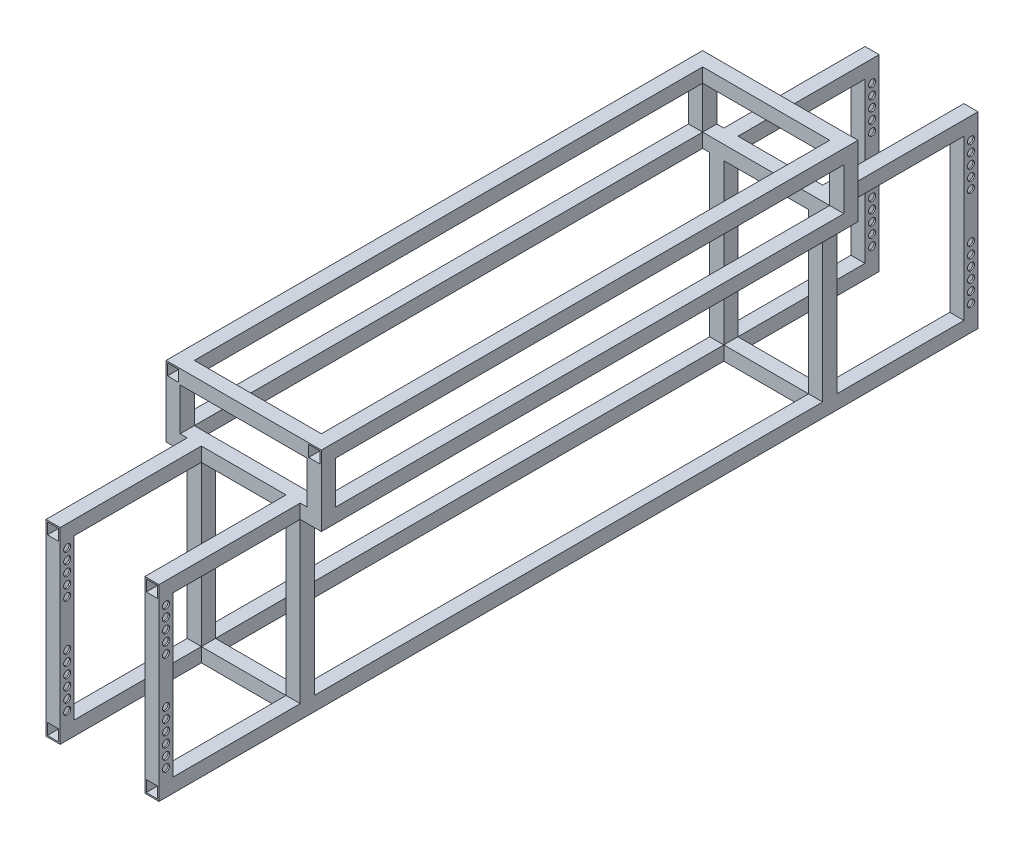
SolidWorks part; units mm, degrees
ref_plane "Płaszczyzna przednia" through (0, 0, 0) normal (0, 0, 1) x (1, 0, 0)
ref_plane "Płaszczyzna górna" through (0, 0, 0) normal (0, 1, 0) x (1, 0, 0)
ref_plane "Płaszczyzna prawa" through (0, 0, 0) normal (1, 0, 0) x (0, 0, -1)
sketch "Szkic1" plane through (0, 0, 0) normal (0, 0, 1) x (1, 0, 0)
  line L0 (-8, 8) -> (8, 8)
  line L1 (-10, -10) -> (10, -10)
  line L2 (-10, -10) -> (-10, 10)
  line L3 (-10, 10) -> (10, 10)
  line L4 (10, -10) -> (10, 10)
  line L5 (-10, -10) -> (10, 10) construction
  line L6 (-10, 10) -> (10, -10) construction
  line L7 (8, -8) -> (8, 8)
  line L8 (-8, -8) -> (8, -8)
  line L9 (-8, -8) -> (-8, 8)
  point P0 (0, 0)
  dimension "D1" = 20
  dimension "D2" = 20
  dimension "D3" = 2
extrude "Dodanie-wyciągnięcie1" add sketch "Szkic1" along normal blind 760
sketch "Szkic2" plane through (10, 0, 0) normal (1, 0, 0) x (0, 0, -1)
  line L0 (-760, -10) -> (0, -10) construction
  line L1 (-760, 10) -> (-740, 10)
  line L2 (-760, 10) -> (-760, -10)
  line L3 (-760, -10) -> (-740, -10)
  line L4 (-740, 10) -> (-740, -10)
  line L5 (-758, 8) -> (-742, 8)
  line L6 (-742, 8) -> (-742, -8)
  line L7 (-758, -8) -> (-742, -8)
  line L8 (-758, 8) -> (-758, -8)
  dimension "D1" = 20
  dimension "D2" = 2
extrude "Dodanie-wyciągnięcie2" add sketch "Szkic2" along normal blind 180
sketch "Szkic3" plane through (10, 0, 0) normal (1, 0, 0) x (0, 0, -1)
  line L0 (-740, -10) -> (0, -10) construction
  line L1 (0, 10) -> (-20, 10)
  line L2 (0, 10) -> (0, -10)
  line L3 (0, -10) -> (-20, -10)
  line L4 (-20, 10) -> (-20, -10)
  line L5 (-2, 8) -> (-18, 8)
  line L6 (-18, 8) -> (-18, -8)
  line L7 (-2, -8) -> (-18, -8)
  line L8 (-2, 8) -> (-2, -8)
  dimension "D1" = 20
  dimension "D2" = 2
extrude "Dodanie-wyciągnięcie3" add sketch "Szkic3" along normal blind 180
sketch "Szkic4" plane through (0, 0, 760) normal (0, 0, 1) x (1, 0, 0)
  line L0 (192, 8) -> (208, 8)
  line L1 (190, 10) -> (210, 10)
  line L2 (190, 10) -> (190, -10)
  line L3 (190, -10) -> (210, -10)
  line L4 (210, 10) -> (210, -10)
  line L5 (208, 8) -> (208, -8)
  line L6 (192, -8) -> (208, -8)
  line L7 (192, 8) -> (192, -8)
  dimension "D1" = 20
  dimension "D2" = 20
  dimension "D3" = 2
extrude "Dodanie-wyciągnięcie4" add sketch "Szkic4" against normal blind 760
sketch "Szkic5" plane through (0, -10, 0) normal (0, -1, 0) x (1, 0, 0)
  line L0 (-8, 758) -> (8, 758)
  line L1 (-10, 760) -> (10, 760)
  line L2 (-10, 760) -> (-10, 740)
  line L3 (-10, 740) -> (10, 740)
  line L4 (10, 760) -> (10, 740)
  line L5 (210, 760) -> (190, 760)
  line L6 (210, 760) -> (210, 740)
  line L7 (210, 740) -> (190, 740)
  line L8 (190, 760) -> (190, 740)
  line L9 (-10, 0) -> (10, 0)
  line L10 (-10, 0) -> (-10, 20)
  line L11 (-10, 20) -> (10, 20)
  line L12 (10, 0) -> (10, 20)
  line L13 (210, 0) -> (190, 0)
  line L14 (210, 0) -> (210, 20)
  line L15 (210, 20) -> (190, 20)
  line L16 (190, 0) -> (190, 20)
  line L17 (8, 758) -> (8, 742)
  line L18 (-8, 742) -> (8, 742)
  line L19 (-8, 758) -> (-8, 742)
  line L20 (208, 758) -> (192, 758)
  line L21 (192, 758) -> (192, 742)
  line L22 (208, 742) -> (192, 742)
  line L23 (208, 758) -> (208, 742)
  line L24 (208, 18) -> (192, 18)
  line L25 (192, 2) -> (192, 18)
  line L26 (208, 2) -> (192, 2)
  line L27 (208, 2) -> (208, 18)
  line L28 (-8, 18) -> (8, 18)
  line L29 (8, 2) -> (8, 18)
  line L30 (-8, 2) -> (8, 2)
  line L31 (-8, 2) -> (-8, 18)
  dimension "D1" = 2
extrude "Dodanie-wyciągnięcie5" add sketch "Szkic5" along normal blind 80
sketch "Szkic6" plane through (0, 0, 20) normal (0, 0, 1) x (1, 0, 0)
  line L0 (210, -90) -> (210, 10) construction
  line L1 (210, -90) -> (190, -90)
  line L2 (210, -90) -> (210, -70)
  line L3 (210, -70) -> (190, -70)
  line L4 (190, -90) -> (190, -70)
  line L5 (190, -90) -> (190, -10) construction
  line L6 (-10, 10) -> (-10, -90) construction
  line L7 (-10, -90) -> (10, -90)
  line L8 (-10, -90) -> (-10, -70)
  line L9 (-10, -70) -> (10, -70)
  line L10 (10, -90) -> (10, -70)
  line L11 (10, -90) -> (10, -10) construction
  line L12 (10, -10) -> (190, -10) construction
  line L13 (208, -72) -> (192, -72)
  line L14 (192, -88) -> (192, -72)
  line L15 (208, -88) -> (192, -88)
  line L16 (208, -88) -> (208, -72)
  line L17 (-8, -72) -> (8, -72)
  line L18 (8, -88) -> (8, -72)
  line L19 (-8, -88) -> (8, -88)
  line L20 (-8, -88) -> (-8, -72)
  dimension "D1" = 20
  dimension "D2" = 20
  dimension "D3" = 60
  dimension "D4" = 60
  dimension "D5" = 2
extrude "Dodanie-wyciągnięcie6" add sketch "Szkic6" along normal up to next
sketch "Szkic7" plane through (10, 0, 0) normal (1, 0, 0) x (0, 0, -1)
  line L0 (-2, -88) -> (-2, -72)
  line L1 (-760, -90) -> (-740, -90)
  line L2 (-760, -90) -> (-760, -70)
  line L3 (-760, -70) -> (-740, -70)
  line L4 (-740, -90) -> (-740, -70)
  line L5 (0, -90) -> (-20, -90)
  line L6 (0, -90) -> (0, -70)
  line L7 (0, -70) -> (-20, -70)
  line L8 (-20, -90) -> (-20, -70)
  line L9 (-2, -72) -> (-18, -72)
  line L10 (-18, -88) -> (-18, -72)
  line L11 (-2, -88) -> (-18, -88)
  line L12 (-758, -72) -> (-742, -72)
  line L13 (-742, -88) -> (-742, -72)
  line L14 (-758, -88) -> (-742, -88)
  line L15 (-758, -88) -> (-758, -72)
  dimension "D1" = 2
extrude "Dodanie-wyciągnięcie7" add sketch "Szkic7" along normal up to next
sketch "Szkic8" plane through (0, 0, 0) normal (0, 0, -1) x (-1, 0, 0)
  line L0 (-190, -70) -> (-10, -70) construction
  line L1 (-40, -70) -> (-20, -70)
  line L2 (-40, -70) -> (-40, -90)
  line L3 (-40, -90) -> (-20, -90)
  line L4 (-20, -70) -> (-20, -90)
  line L5 (10, -90) -> (-210, -90) construction
  line L6 (-210, -90) -> (-210, 10) construction
  line L7 (-180, -70) -> (-160, -70)
  line L8 (-180, -70) -> (-180, -90)
  line L9 (-180, -90) -> (-160, -90)
  line L10 (-160, -70) -> (-160, -90)
  line L12 (-178, -72) -> (-178, -88)
  line L13 (-178, -88) -> (-162, -88)
  line L14 (-162, -72) -> (-162, -88)
  line L15 (-178, -72) -> (-162, -72)
  line L16 (-38, -72) -> (-22, -72)
  line L17 (-22, -72) -> (-22, -88)
  line L18 (-38, -88) -> (-22, -88)
  line L19 (-38, -72) -> (-38, -88)
  dimension "D1" = 20
  dimension "D2" = 20
  dimension "D3" = 120
  dimension "D4" = 30
  dimension "D5" = 2
extrude "Dodanie-wyciągnięcie8" add sketch "Szkic8" along normal blind 200
sketch "Szkic9" plane through (0, 0, 760) normal (0, 0, 1) x (1, 0, 0)
  line L0 (38, -88) -> (38, -72)
  line L1 (180, -90) -> (160, -90)
  line L2 (180, -90) -> (180, -70)
  line L3 (180, -70) -> (160, -70)
  line L4 (160, -90) -> (160, -70)
  line L5 (40, -90) -> (20, -90)
  line L6 (40, -90) -> (40, -70)
  line L7 (40, -70) -> (20, -70)
  line L8 (20, -90) -> (20, -70)
  line L9 (38, -72) -> (22, -72)
  line L10 (22, -88) -> (22, -72)
  line L11 (38, -88) -> (22, -88)
  line L12 (162, -88) -> (162, -72)
  line L13 (178, -72) -> (162, -72)
  line L14 (178, -88) -> (178, -72)
  line L15 (178, -88) -> (162, -88)
  dimension "D1" = 2
extrude "Dodanie-wyciągnięcie9" add sketch "Szkic9" along normal blind 200
sketch "Szkic10" plane through (0, -90, 0) normal (0, -1, 0) x (1, 0, 0)
  line L0 (160, 960) -> (160, 760) construction
  line L1 (180, 960) -> (160, 960)
  line L2 (180, 960) -> (180, 940)
  line L3 (180, 940) -> (160, 940)
  line L4 (160, 960) -> (160, 940)
  line L5 (20, 960) -> (20, 760) construction
  line L6 (40, 960) -> (20, 960)
  line L7 (40, 960) -> (40, 940)
  line L8 (40, 940) -> (20, 940)
  line L9 (20, 960) -> (20, 940)
  line L10 (38, 942) -> (22, 942)
  line L11 (22, 958) -> (22, 942)
  line L12 (38, 958) -> (22, 958)
  line L13 (38, 958) -> (38, 942)
  line L14 (178, 942) -> (162, 942)
  line L15 (162, 958) -> (162, 942)
  line L16 (178, 958) -> (162, 958)
  line L17 (178, 958) -> (178, 942)
  dimension "D1" = 20
  dimension "D2" = 20
  dimension "D3" = 2
extrude "Dodanie-wyciągnięcie10" add sketch "Szkic10" along normal blind 226
sketch3d "Szkic 3D1" plane through (0, 0, 0) normal (0, 0, 1) x (1, 0, 0)
  dimension "D1" = 360
ref_plane "Płaszczyzna1" through (0, 0, 380) normal (0, 0, -1) x (-1, 0, 0)
mirror "Lustro1" about plane through (0, 0, 380) normal (0, 0, -1) of "Dodanie-wyciągnięcie10"
ref_plane "Płaszczyzna2" through (0, -203, 0) normal (0, -1, 0) x (-1, 0, 0)
mirror "Lustro2" about plane through (0, -203, 0) normal (0, -1, 0) of "Dodanie-wyciągnięcie9", "Dodanie-wyciągnięcie8"
sketch "Szkic11" plane through (0, -90, 0) normal (0, -1, 0) x (1, 0, 0)
  line L0 (40, 0) -> (20, 0) construction
  line L1 (20, 0) -> (40, 0)
  line L2 (20, 0) -> (20, 20)
  line L3 (20, 20) -> (40, 20)
  line L4 (40, 0) -> (40, 20)
  line L5 (190, 20) -> (10, 20) construction
  line L6 (40, 760) -> (20, 760) construction
  line L7 (160, 0) -> (180, 0)
  line L8 (160, 0) -> (160, 20)
  line L9 (160, 20) -> (180, 20)
  line L10 (180, 0) -> (180, 20)
  line L11 (20, 760) -> (40, 760)
  line L12 (20, 760) -> (20, 740)
  line L13 (20, 740) -> (40, 740)
  line L14 (40, 760) -> (40, 740)
  line L15 (20, 960) -> (20, 760) construction
  line L16 (190, 740) -> (10, 740) construction
  line L17 (-10, 760) -> (-10, 0) construction
  line L18 (160, 760) -> (180, 760)
  line L19 (160, 760) -> (160, 740)
  line L20 (160, 740) -> (180, 740)
  line L21 (180, 760) -> (180, 740)
  line L22 (210, 0) -> (210, 760) construction
  line L23 (38, 758) -> (38, 742)
  line L24 (22, 742) -> (38, 742)
  line L25 (22, 758) -> (22, 742)
  line L26 (22, 758) -> (38, 758)
  line L27 (178, 758) -> (178, 742)
  line L28 (162, 742) -> (178, 742)
  line L29 (162, 758) -> (162, 742)
  line L30 (162, 758) -> (178, 758)
  line L31 (178, 2) -> (178, 18)
  line L32 (162, 18) -> (178, 18)
  line L33 (162, 2) -> (162, 18)
  line L34 (162, 2) -> (178, 2)
  line L35 (38, 2) -> (38, 18)
  line L36 (22, 18) -> (38, 18)
  line L37 (22, 2) -> (22, 18)
  line L38 (22, 2) -> (38, 2)
  dimension "D1" = 20
  dimension "D2" = 30
  dimension "D3" = 30
  dimension "D4" = 2
extrude "Dodanie-wyciągnięcie11" add sketch "Szkic11" along normal blind 246
sketch "Szkic12" plane through (0, 0, 740) normal (0, 0, -1) x (-1, 0, 0)
  line L0 (-160, -336) -> (-160, -70) construction
  line L1 (-180, -336) -> (-160, -336)
  line L2 (-180, -336) -> (-180, -316)
  line L3 (-180, -316) -> (-160, -316)
  line L4 (-160, -336) -> (-160, -316)
  line L5 (-20, -336) -> (-20, -70) construction
  line L6 (-40, -336) -> (-20, -336)
  line L7 (-40, -336) -> (-40, -316)
  line L8 (-40, -316) -> (-20, -316)
  line L9 (-20, -336) -> (-20, -316)
  line L10 (-178, -318) -> (-162, -318)
  line L11 (-162, -334) -> (-162, -318)
  line L12 (-178, -334) -> (-162, -334)
  line L13 (-178, -334) -> (-178, -318)
  line L14 (-38, -318) -> (-22, -318)
  line L15 (-22, -334) -> (-22, -318)
  line L16 (-38, -334) -> (-22, -334)
  line L17 (-38, -334) -> (-38, -318)
  dimension "D1" = 20
  dimension "D2" = 20
  dimension "D3" = 2
extrude "Dodanie-wyciągnięcie12" add sketch "Szkic12" along normal up to next
sketch "Szkic13" plane through (40, 0, 0) normal (1, 0, 0) x (0, 0, -1)
  line L0 (200, -336) -> (-960, -336) construction
  line L1 (-760, -316) -> (-740, -316)
  line L2 (-760, -316) -> (-760, -336)
  line L3 (-760, -336) -> (-740, -336)
  line L4 (-740, -316) -> (-740, -336)
  line L5 (-758, -318) -> (-742, -318)
  line L6 (-742, -318) -> (-742, -334)
  line L7 (-758, -334) -> (-742, -334)
  line L8 (-758, -318) -> (-758, -334)
  dimension "D1" = 20
  dimension "D2" = 2
extrude "Dodanie-wyciągnięcie13" add sketch "Szkic13" along normal up to next
mirror "Lustro3" about plane through (0, 0, 380) normal (0, 0, -1) of "Dodanie-wyciągnięcie13"
sketch "Szkic14" plane through (180, 0, 0) normal (1, 0, 0) x (0, 0, -1)
  line L0 (-960, -70) -> (-760, -70) construction
  line L1 (-960, -336) -> (-960, -70) construction
  circle A0 centre (-950, -100) radius 5
  circle A1 centre (-950, -115) radius 5
  circle A2 centre (-950, -130) radius 5
  circle A3 centre (-950, -145) radius 5
  circle A4 centre (-950, -160) radius 5
  dimension "D1" = 10
  dimension "D2" = 30
  dimension "D3" = 10
  dimension "D4" = 5
extrude "Wytnij-wyciągnięcie1" cut sketch "Szkic14" against normal blind 180
mirror "Lustro4" about plane through (0, 0, 380) normal (0, 0, -1) of "Wytnij-wyciągnięcie1"
sketch "Szkic15" plane through (180, 0, 0) normal (1, 0, 0) x (0, 0, -1)
  line L0 (200, -336) -> (-960, -336) construction
  line L1 (-960, -336) -> (-960, -70) construction
  circle A0 centre (-950, -300) radius 5
  circle A1 centre (-950, -285) radius 5
  circle A2 centre (-950, -270) radius 5
  circle A3 centre (-950, -255) radius 5
  circle A4 centre (-950, -240) radius 5
  circle A5 centre (-950, -225) radius 5
  dimension "D1" = 10
  dimension "D2" = 36
  dimension "D3" = 10
  dimension "D4" = 6
extrude "Wytnij-wyciągnięcie2" cut sketch "Szkic15" against normal blind 180
mirror "Lustro5" about plane through (0, 0, 380) normal (0, 0, -1) of "Wytnij-wyciągnięcie2"
ref_plane "Płaszczyzna3" through (0, -76.2132, -23.9225) normal (0, 0.9541, 0.2995) x (1, 0, 0)
sketch "Szkic16" plane through (0, 0, 20) normal (0, 0, 1) x (1, 0, 0)
  line L1 (160, -70) -> (180, -70)
  line L2 (160, -70) -> (160, -90)
  line L3 (160, -90) -> (180, -90)
  line L4 (180, -70) -> (180, -90)
  line L5 (20, -70) -> (40, -70)
  line L6 (20, -70) -> (20, -90)
  line L7 (20, -90) -> (40, -90)
  line L8 (40, -70) -> (40, -90)
  point P12 (0, 0)
  point P13 (0, 0)
  point P14 (0, 0)
  point P15 (0, 0)
  point P16 (0, 0)
  point P17 (0, 0)
  point P18 (0, 0)
  point P19 (0, 0)
  point P20 (0, 0)
sketch "Szkic17" plane through (0, 0, 740) normal (0, 0, -1) x (-1, 0, 0)
  line L0 (-180, -70) -> (-180, -336) construction
  line L1 (-160, -316) -> (-180, -316)
  line L2 (-160, -316) -> (-160, -296)
  line L3 (-160, -296) -> (-180, -296)
  line L4 (-180, -316) -> (-180, -296)
  line L5 (-20, -336) -> (-20, -70) construction
  line L6 (-40, -316) -> (-20, -316)
  line L7 (-40, -316) -> (-40, -296)
  line L8 (-40, -296) -> (-20, -296)
  line L9 (-20, -316) -> (-20, -296)
  point P14 (0, 0)
  point P15 (0, 0)
  dimension "D1" = 20
  dimension "D2" = 20
